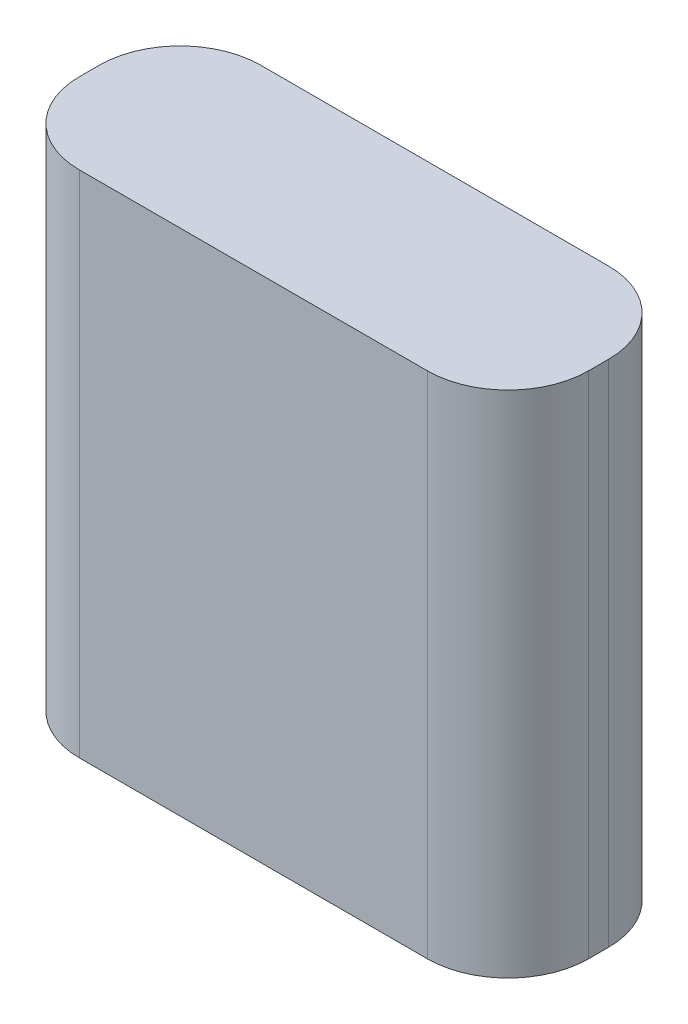
SolidWorks part; units mm, degrees
ref_plane "Front Plane" through (0, 0, 0) normal (0, 0, 1) x (1, 0, 0)
ref_plane "Top Plane" through (0, 0, 0) normal (0, 1, 0) x (1, 0, 0)
ref_plane "Right Plane" through (0, 0, 0) normal (1, 0, 0) x (0, 0, -1)
sketch "Sketch1" plane through (0, 0, 0) normal (0, 1, 0) x (1, 0, 0)
  line L1 (-40.132, -14.2875) -> (40.132, -14.2875)
  line L2 (-40.132, -14.2875) -> (-40.132, 14.2875)
  line L3 (-40.132, 14.2875) -> (40.132, 14.2875)
  line L4 (40.132, -14.2875) -> (40.132, 14.2875)
  line L5 (-40.132, -14.2875) -> (40.132, 14.2875) construction
  line L6 (-40.132, 14.2875) -> (40.132, -14.2875) construction
  point P0 (0, 0)
  dimension "D1" = 28.575
  dimension "D2" = 80.264
extrude "Boss-Extrude1" add sketch "Sketch1" along normal blind 80.264
sketch "Sketch2" plane through (0, 80.264, 0) normal (0, 1, 0) x (1, 0, 0)
  line L0 (-40.132, 0) -> (40.132, 0)
  line L1 (-40.132, 14.2875) -> (-40.132, -14.2875) construction
  line L2 (40.132, -14.2875) -> (40.132, 14.2875) construction
fillet "Fillet1" radius 12.7 4 edges at (-40.132, 40.132, 14.2875) (-40.132, 40.132, -14.2875) (40.132, 40.132, 14.2875) (40.132, 40.132, -14.2875)
